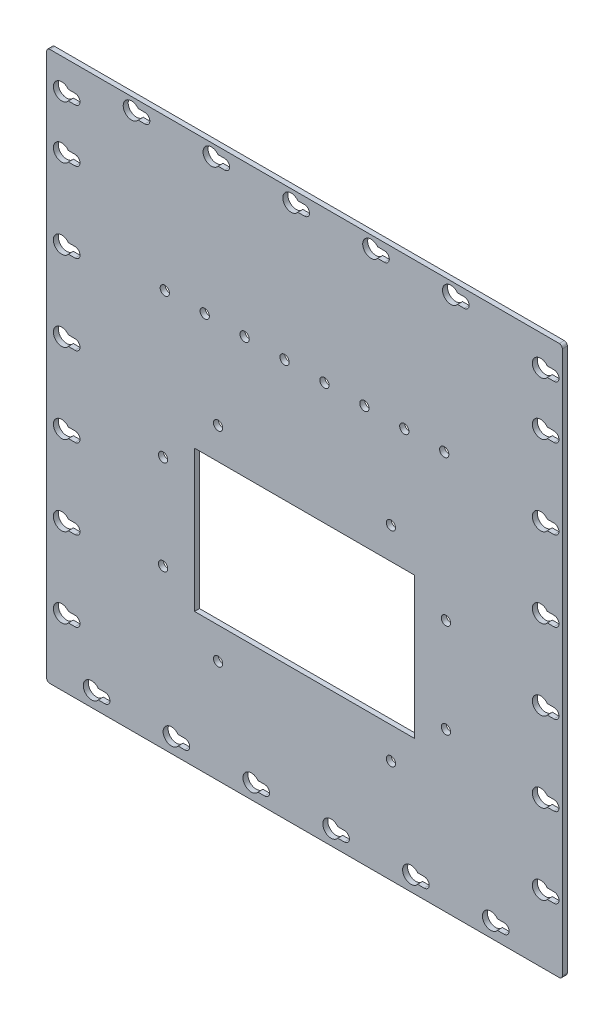
SolidWorks part; units mm, degrees
material "6061 Alloy"
ref_plane "Front Plane" through (0, 0, 0) normal (0, 0, 1) x (1, 0, 0)
ref_plane "Top Plane" through (0, 0, 0) normal (0, 1, 0) x (1, 0, 0)
ref_plane "Right Plane" through (0, 0, 0) normal (1, 0, 0) x (0, 0, -1)
sketch "Sketch1" plane through (0, 0, 0) normal (0, 0, 1) x (1, 0, 0)
  line L0 (0, 0) -> (0, -174.745)
  line L3 (0, -174.745) -> (165.1, -174.745)
  line L5 (0, 0) -> (165.1, 0)
  line L6 (165.1, -174.745) -> (165.1, 0)
  line L7 (82.55, 0) -> (82.55, -174.745) construction
  line L8 (31.75, -2.2625) -> (29.6344, -2.2625)
  line L9 (31.75, -5.4375) -> (29.6344, -5.4375)
  line L10 (9.525, -24.9325) -> (7.4094, -24.9325)
  line L11 (9.525, -28.1075) -> (7.4094, -28.1075)
  line L12 (161.925, -24.9325) -> (159.8094, -24.9325)
  line L13 (161.925, -28.1075) -> (159.8094, -28.1075)
  line L14 (57.15, -2.2625) -> (55.0344, -2.2625)
  line L15 (57.15, -5.4375) -> (55.0344, -5.4375)
  line L16 (82.55, -2.2625) -> (80.4344, -2.2625)
  line L17 (82.55, -5.4375) -> (80.4344, -5.4375)
  line L18 (107.95, -2.2625) -> (105.8344, -2.2625)
  line L19 (107.95, -5.4375) -> (105.8344, -5.4375)
  line L20 (133.35, -2.2625) -> (131.2344, -2.2625)
  line L21 (133.35, -5.4375) -> (131.2344, -5.4375)
  line L22 (9.525, -50.3325) -> (7.4094, -50.3325)
  line L23 (9.525, -53.5075) -> (7.4094, -53.5075)
  line L24 (161.925, -50.3325) -> (159.8094, -50.3325)
  line L25 (161.925, -53.5075) -> (159.8094, -53.5075)
  line L26 (9.525, -75.7325) -> (7.4094, -75.7325)
  line L27 (9.525, -78.9075) -> (7.4094, -78.9075)
  line L28 (161.925, -75.7325) -> (159.8094, -75.7325)
  line L29 (161.925, -78.9075) -> (159.8094, -78.9075)
  line L30 (9.525, -101.1325) -> (7.4094, -101.1325)
  line L31 (9.525, -104.3075) -> (7.4094, -104.3075)
  line L32 (161.925, -101.1325) -> (159.8094, -101.1325)
  line L33 (161.925, -104.3075) -> (159.8094, -104.3075)
  line L34 (9.525, -126.5325) -> (7.4094, -126.5325)
  line L35 (9.525, -129.7075) -> (7.4094, -129.7075)
  line L36 (161.925, -126.5325) -> (159.8094, -126.5325)
  line L37 (161.925, -129.7075) -> (159.8094, -129.7075)
  line L38 (9.525, -151.9325) -> (7.4094, -151.9325)
  line L39 (9.525, -155.1075) -> (7.4094, -155.1075)
  line L40 (161.925, -151.9325) -> (159.8094, -151.9325)
  line L41 (161.925, -155.1075) -> (159.8094, -155.1075)
  line L42 (19.05, -168.395) -> (16.9344, -168.395)
  line L43 (19.05, -171.57) -> (16.9344, -171.57)
  line L44 (44.45, -168.395) -> (42.3344, -168.395)
  line L45 (44.45, -171.57) -> (42.3344, -171.57)
  line L46 (69.85, -168.395) -> (67.7344, -168.395)
  line L47 (69.85, -171.57) -> (67.7344, -171.57)
  line L48 (95.25, -168.395) -> (93.1344, -168.395)
  line L49 (95.25, -171.57) -> (93.1344, -171.57)
  line L50 (120.65, -168.395) -> (118.5344, -168.395)
  line L51 (120.65, -171.57) -> (118.5344, -171.57)
  line L52 (146.05, -168.395) -> (143.9344, -168.395)
  line L53 (146.05, -171.57) -> (143.9344, -171.57)
  line L54 (0.5, 0) -> (0.5, -174.745)
  line L55 (164.6, -174.745) -> (164.6, 0)
  line L56 (0.5, -174.745) -> (164.6, -174.745)
  line L57 (9.525, -8.1) -> (7.4094, -8.1)
  line L58 (9.525, -11.275) -> (7.4094, -11.275)
  line L59 (161.925, -8.1) -> (159.8094, -8.1)
  line L60 (161.925, -11.275) -> (159.8094, -11.275)
  circle A41 centre (9.525, -153.52) radius 1.5875
  circle A42 centre (19.05, -169.9825) radius 1.5875
  circle A43 centre (9.525, -128.12) radius 1.5875
  circle A44 centre (9.525, -102.72) radius 1.5875
  circle A45 centre (9.525, -77.32) radius 1.5875
  circle A46 centre (9.525, -51.92) radius 1.5875
  circle A47 centre (9.525, -26.52) radius 1.5875
  circle A49 centre (44.45, -169.9825) radius 1.5875
  circle A50 centre (69.85, -169.9825) radius 1.5875
  circle A51 centre (95.25, -169.9825) radius 1.5875
  circle A52 centre (120.65, -169.9825) radius 1.5875
  circle A68 centre (146.05, -169.9825) radius 1.5875
  circle A69 centre (107.95, -3.85) radius 1.5875
  circle A70 centre (82.55, -3.85) radius 1.5875
  circle A71 centre (57.15, -3.85) radius 1.5875
  circle A72 centre (9.525, -1.12) radius 1.5875 [skipped]
  circle A73 centre (133.35, -3.85) radius 1.5875
  circle A74 centre (31.75, -3.85) radius 1.5875
  circle A75 centre (161.925, -26.52) radius 1.5875
  circle A76 centre (161.925, -51.92) radius 1.5875
  circle A77 centre (161.925, -77.32) radius 1.5875
  circle A78 centre (161.925, -102.72) radius 1.5875
  circle A79 centre (161.925, -128.12) radius 1.5875
  circle A80 centre (161.925, -153.52) radius 1.5875
  circle A81 centre (27.5125, -3.85) radius 2.65
  circle A83 centre (5.2875, -26.52) radius 2.65
  circle A84 centre (157.6875, -26.52) radius 2.65
  circle A85 centre (52.9125, -3.85) radius 2.65
  circle A86 centre (78.3125, -3.85) radius 2.65
  circle A87 centre (103.7125, -3.85) radius 2.65
  circle A88 centre (129.1125, -3.85) radius 2.65
  circle A89 centre (5.2875, -51.92) radius 2.65
  circle A90 centre (157.6875, -51.92) radius 2.65
  circle A91 centre (5.2875, -77.32) radius 2.65
  circle A92 centre (157.6875, -77.32) radius 2.65
  circle A93 centre (5.2875, -102.72) radius 2.65
  circle A94 centre (157.6875, -102.72) radius 2.65
  circle A95 centre (5.2875, -128.12) radius 2.65
  circle A96 centre (157.6875, -128.12) radius 2.65
  circle A97 centre (5.2875, -153.52) radius 2.65
  circle A98 centre (157.6875, -153.52) radius 2.65
  circle A99 centre (14.8125, -169.9825) radius 2.65
  circle A100 centre (40.2125, -169.9825) radius 2.65
  circle A101 centre (65.6125, -169.9825) radius 2.65
  circle A102 centre (91.0125, -169.9825) radius 2.65
  circle A103 centre (116.4125, -169.9825) radius 2.65
  circle A104 centre (141.8125, -169.9825) radius 2.65
  circle A107 centre (9.525, -9.6875) radius 1.5875
  circle A108 centre (5.2875, -9.6875) radius 2.65
  circle A109 centre (161.925, -9.6875) radius 1.5875
  circle A110 centre (157.6875, -9.6875) radius 2.65
  dimension "D3" = 3.175
  dimension "D8" = 3.175
  dimension "D21" = 5.3
  dimension "D33" = 5.3
  dimension "D1" = 165.1
  dimension "D2" = 174.745
  dimension "D5" = 9.525
  dimension "D4" = 21.225
  dimension "D6" = 19.05
  dimension "D7" = 4.7625
  dimension "D9" = 25.4
  dimension "D10" = 25.4
  dimension "D15" = 25.4
  dimension "D12" = 3.85
  dimension "D13" = 31.75
  dimension "D17" = 31.75
  dimension "D18" = 3.175
  dimension "D20" = 25.4
  dimension "D23" = 25.4
  dimension "D25" = 25.4
  dimension "D27" = 25.4
  dimension "D28" = 0.5
  dimension "D29" = 0.5
  dimension "D34" = 16.8325
  dimension "D35" = 5.8375
  dimension "D11" = 7
  dimension "D14" = 5
  dimension "D16" = 5
  dimension "D19" = 6
  dimension "D22" = 5
  dimension "D24" = 6
  dimension "D26" = 6
extrude "Boss-Extrude1" add sketch "Sketch1" along normal blind 1.5875
fillet "Fillet1" radius 1 4 edges at (164.6, 0, 0.7937) (164.6, -174.745, 0.7937) (0.5, -174.745, 0.7937) (0.5, 0, 0.7937)
sketch "Sketch2" plane through (0, 0, 1.5875) normal (0, 0, 1) x (1, 0, 0)
  line L0 (127.55, -94.3725) -> (37.55, -94.3725) construction
  line L1 (47.55, -86.8725) -> (117.55, -86.8725)
  line L3 (47.55, -131.8725) -> (117.55, -131.8725)
  line L5 (55.05, -76.8725) -> (110.05, -76.8725) construction
  line L6 (55.05, -76.8725) -> (55.05, -141.8725) construction
  line L7 (55.05, -141.8725) -> (110.05, -141.8725) construction
  line L8 (110.05, -76.8725) -> (110.05, -141.8725) construction
  line L9 (37.55, -94.3725) -> (37.55, -124.3725) construction
  line L10 (37.55, -124.3725) -> (127.55, -124.3725) construction
  line L11 (127.55, -124.3725) -> (127.55, -94.3725) construction
  line L12 (82.55, -86.8725) -> (82.55, -131.8725) construction
  line L13 (82.55, 0) -> (82.55, -174.745) construction
  line L14 (1.5, 0) -> (163.6, 0) construction
  line L15 (1.5, -174.745) -> (163.6, -174.745) construction
  line L16 (47.55, -126.8725) -> (117.55, -126.8725) construction
  line L17 (0.5, -87.3725) -> (164.6, -87.3725) construction
  line L18 (0.5, -1) -> (0.5, -173.745) construction
  line L19 (164.6, -173.745) -> (164.6, -1) construction
  line L20 (117.55, -86.8725) -> (117.55, -126.8725)
  line L21 (117.55, -126.8725) -> (117.55, -131.8725)
  line L22 (47.55, -86.8725) -> (47.55, -126.8725)
  line L23 (47.55, -126.8725) -> (47.55, -131.8725)
  circle A0 centre (110.05, -76.8725) radius 1.4732
  circle A1 centre (55.05, -76.8725) radius 1.4732
  circle A2 centre (127.55, -94.3725) radius 1.4732
  circle A3 centre (127.55, -124.3725) radius 1.4732
  circle A4 centre (55.05, -141.8725) radius 1.4732
  circle A5 centre (110.05, -141.8725) radius 1.4732
  circle A6 centre (37.55, -124.3725) radius 1.4732
  circle A7 centre (37.55, -94.3725) radius 1.4732
  point P37 (82.55, -109.3725)
  dimension "D11" = 2.9464
  dimension "D1" = 55
  dimension "D2" = 70
  dimension "D9" = 0
  dimension "D7" = 40
  dimension "D3" = 5
  dimension "D4" = 10
  dimension "D5" = 10
  dimension "D6" = 7.5
  dimension "D8" = 30
  dimension "D12" = 15
  dimension "D13" = 10
  dimension "D14" = 10
  dimension "D10" = 22
extrude "Cut-Extrude1" cut sketch "Sketch2" against normal blind 10
sketch "Sketch3" plane through (0, 0, 1.5875) normal (0, 0, 1) x (1, 0, 0)
  line L0 (82.55, -86.8725) -> (82.55, -131.8725) construction
  line L1 (47.55, -86.8725) -> (117.55, -86.8725) construction
  line L2 (47.55, -131.8725) -> (117.55, -131.8725) construction
sketch "Heat Strap Connections" plane through (0, 0, 1.5875) normal (0, 0, 1) x (1, 0, 0)
  line L0 (1.5, 0) -> (163.6, 0) construction
  line L1 (33.1, -45) -> (43.1, -45) construction
  line L2 (33.1, -45) -> (33.1, -57.7) construction
  line L3 (33.1, -57.7) -> (43.1, -57.7) construction
  line L4 (43.1, -45) -> (43.1, -57.7) construction
  line L6 (45.8, -57.7) -> (55.8, -57.7) construction
  line L7 (55.8, -45) -> (55.8, -57.7) construction
  line L8 (45.8, -45) -> (55.8, -45) construction
  line L9 (45.8, -45) -> (45.8, -57.7) construction
  line L10 (58.5, -57.7) -> (68.5, -57.7) construction
  line L11 (68.5, -45) -> (68.5, -57.7) construction
  line L12 (58.5, -45) -> (68.5, -45) construction
  line L13 (58.5, -45) -> (58.5, -57.7) construction
  line L14 (71.2, -57.7) -> (81.2, -57.7) construction
  line L15 (81.2, -45) -> (81.2, -57.7) construction
  line L16 (71.2, -45) -> (81.2, -45) construction
  line L17 (71.2, -45) -> (71.2, -57.7) construction
  line L18 (83.9, -57.7) -> (93.9, -57.7) construction
  line L19 (93.9, -45) -> (93.9, -57.7) construction
  line L20 (83.9, -45) -> (93.9, -45) construction
  line L21 (83.9, -45) -> (83.9, -57.7) construction
  line L22 (96.6, -57.7) -> (106.6, -57.7) construction
  line L23 (106.6, -45) -> (106.6, -57.7) construction
  line L24 (96.6, -45) -> (106.6, -45) construction
  line L25 (96.6, -45) -> (96.6, -57.7) construction
  line L26 (109.3, -57.7) -> (119.3, -57.7) construction
  line L27 (119.3, -45) -> (119.3, -57.7) construction
  line L28 (109.3, -45) -> (119.3, -45) construction
  line L29 (109.3, -45) -> (109.3, -57.7) construction
  line L30 (122, -57.7) -> (132, -57.7) construction
  line L31 (132, -45) -> (132, -57.7) construction
  line L32 (122, -45) -> (132, -45) construction
  line L33 (122, -45) -> (122, -57.7) construction
  line L34 (0.5, -1) -> (0.5, -173.745) construction
  line L39 (47.55, -109.3725) -> (117.55, -109.3725) construction
  line L40 (47.55, -86.8725) -> (47.55, -131.8725) construction
  line L41 (117.55, -86.8725) -> (117.55, -131.8725) construction
  circle A0 centre (38.1, -48.175) radius 1.4732
  circle A1 centre (50.8, -48.175) radius 1.4732
  circle A2 centre (63.5, -48.175) radius 1.4732
  circle A3 centre (76.2, -48.175) radius 1.4732
  circle A4 centre (88.9, -48.175) radius 1.4732
  circle A5 centre (101.6, -48.175) radius 1.4732
  circle A6 centre (114.3, -48.175) radius 1.4732
  circle A7 centre (127, -48.175) radius 1.4732
  point P4 (38.1, -57.7)
  dimension "D4" = 2.9464
  dimension "D1" = 3.175
  dimension "D2" = 10
  dimension "D3" = 12.7
  dimension "D5" = 45
  dimension "D6" = 37.6
  dimension "D8" = 12.7
  dimension "D7" = 8
extrude "Cut-Extrude2" cut sketch "Heat Strap Connections" against normal through all
equation "\"D8@Sketch1\"=\"D3@Sketch1\""
equation "\"D29@Sketch1\"=\"D28@Sketch1\""
equation "\"D5@Sketch2\"=\"D4@Sketch2\""
equation "\"D6@Sketch2\"=(\"D2@Sketch2\"-\"D1@Sketch2\")/2"
equation "\"D12@Sketch2\"=((\"D7@Sketch2\"+\"D3@Sketch2\") - \"D8@Sketch2\")"
equation "\"D13@Sketch2\"=\"D4@Sketch2\""
equation "\"D14@Sketch2\"=\"D13@Sketch2\""
